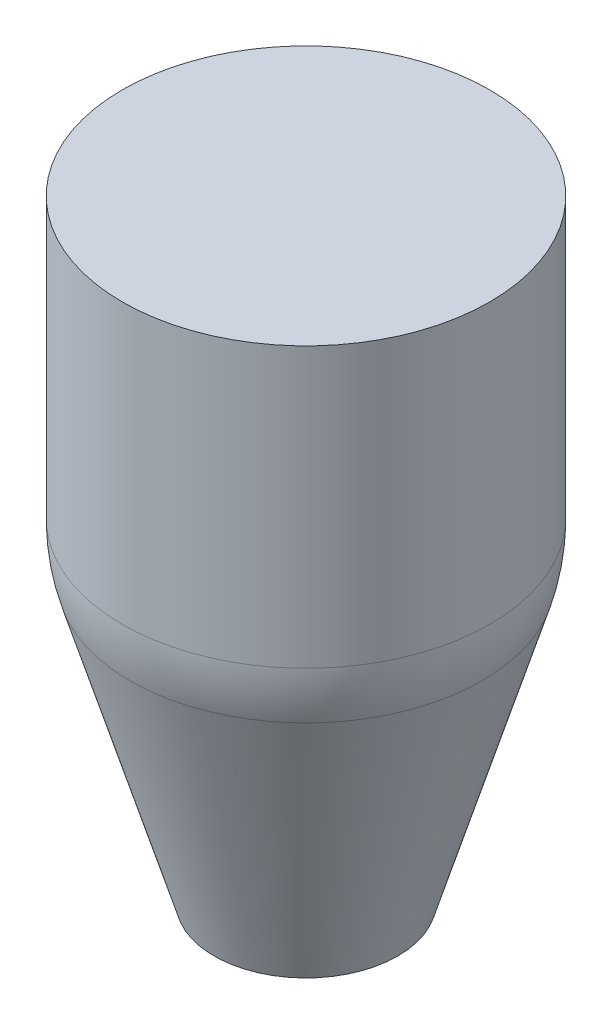
SolidWorks part; units mm, degrees
ref_plane "Front Plane" through (0, 0, 0) normal (0, 0, 1) x (1, 0, 0)
ref_plane "Top Plane" through (0, 0, 0) normal (0, 1, 0) x (1, 0, 0)
ref_plane "Right Plane" through (0, 0, 0) normal (1, 0, 0) x (0, 0, -1)
sketch "Sketch3" plane through (0, 0, 0) normal (0, 0, 1) x (1, 0, 0)
  line L0 (0, 100) -> (0, 0)
  line L1 (0, 0) -> (15, 0)
  line L2 (15, 0) -> (28.7348, 45.7826)
  line L3 (30, 54.4031) -> (30, 100)
  line L4 (30, 100) -> (0, 100)
  arc A0 (28.7348, 45.7826) -> (30, 54.4031) centre (0, 54.4031) ccw
  point P3 (30.8124, 40.7228)
  point P7 (30.8124, 40.7228)
  point P10 (30, 50)
  dimension "D5" = 30
  dimension "D1" = 30
  dimension "D2" = 50
  dimension "D3" = 100
  dimension "D4" = 15
revolve "Revolve1" add sketch "Sketch3" angle 360 about L0
